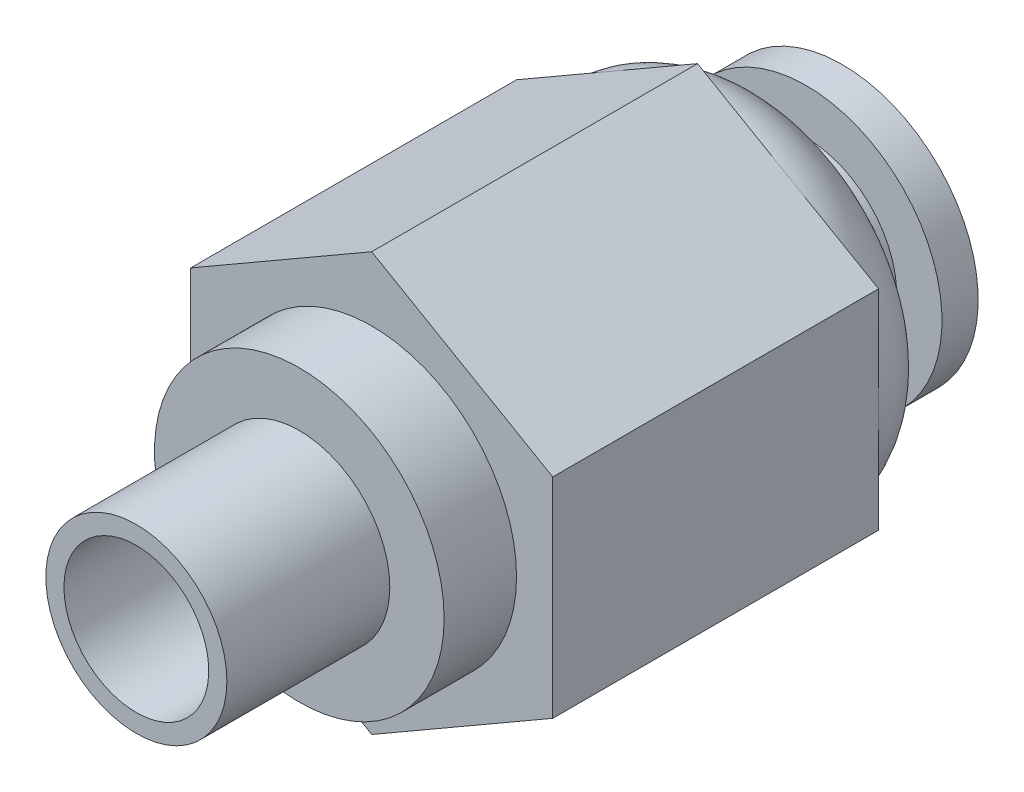
SolidWorks part; units mm, degrees
ref_plane "前视基准面" through (0, 0, 0) normal (0, 0, 1) x (1, 0, 0)
ref_plane "上视基准面" through (0, 0, 0) normal (0, 1, 0) x (1, 0, 0)
ref_plane "右视基准面" through (0, 0, 0) normal (1, 0, 0) x (0, 0, -1)
sketch "草图1" plane through (0, 0, 0) normal (0, 0, 1) x (1, 0, 0)
  line L0 (0, 5.7735) -> (0, 0) construction
  line L1 (5, 2.8868) -> (0, 5.7735)
  line L2 (0, 5.7735) -> (-5, 2.8868)
  line L3 (-5, 2.8868) -> (-5, -2.8868)
  line L4 (-5, -2.8868) -> (0, -5.7735)
  line L5 (0, -5.7735) -> (5, -2.8868)
  line L6 (5, -2.8868) -> (5, 2.8868)
  circle A0 centre (0, 0) radius 5 construction
  dimension "D1" = 10
extrude "凸台-拉伸1" add sketch "草图1" along normal blind 9
sketch "草图2" plane through (0, 0, 9) normal (0, 0, 1) x (1, 0, 0)
  circle A0 centre (0, 0) radius 4
  dimension "D1" = 8
extrude "凸台-拉伸2" add sketch "草图2" along normal blind 2
sketch "草图3" plane through (0, 0, 11) normal (0, 0, 1) x (1, 0, 0)
  circle A0 centre (0, 0) radius 2.5
  dimension "D1" = 5
extrude "凸台-拉伸3" add sketch "草图3" along normal blind 4.5
cosmetic thread "装饰螺纹线1" parameters "D2"=4.11
sketch "草图4" plane through (0, 0, 0) normal (0, 1, 0) x (1, 0, 0)
  line L0 (0, 0) -> (0, 2)
  line L1 (0, 2) -> (3, 2)
  line L2 (5, 0) -> (0, 0) construction
  line L3 (0, 0) -> (5, 0)
  arc A0 (3, 2) -> (5, 0) centre (3, 0) cw
  dimension "D1" = 5
  dimension "D2" = 2
revolve "旋转1" add sketch "草图4" angle 360 about L0
sketch "草图5" plane through (0, 0, -2) normal (0, 0, -1) x (-1, 0, 0)
  circle A0 centre (0, 0) radius 2.5
  dimension "D1" = 5
extrude "凸台-拉伸4" add sketch "草图5" along normal blind 1
sketch "草图6" plane through (0, 0, -3) normal (0, 0, -1) x (-1, 0, 0)
  circle A0 centre (0, 0) radius 3.75
  dimension "D1" = 7.5
extrude "凸台-拉伸5" add sketch "草图6" along normal blind 1
sketch "草图7" plane through (0, 0, -4) normal (0, 0, -1) x (-1, 0, 0)
  circle A0 centre (0, 0) radius 2
  dimension "D1" = 4
extrude "切除-拉伸1" cut sketch "草图7" against normal through all
